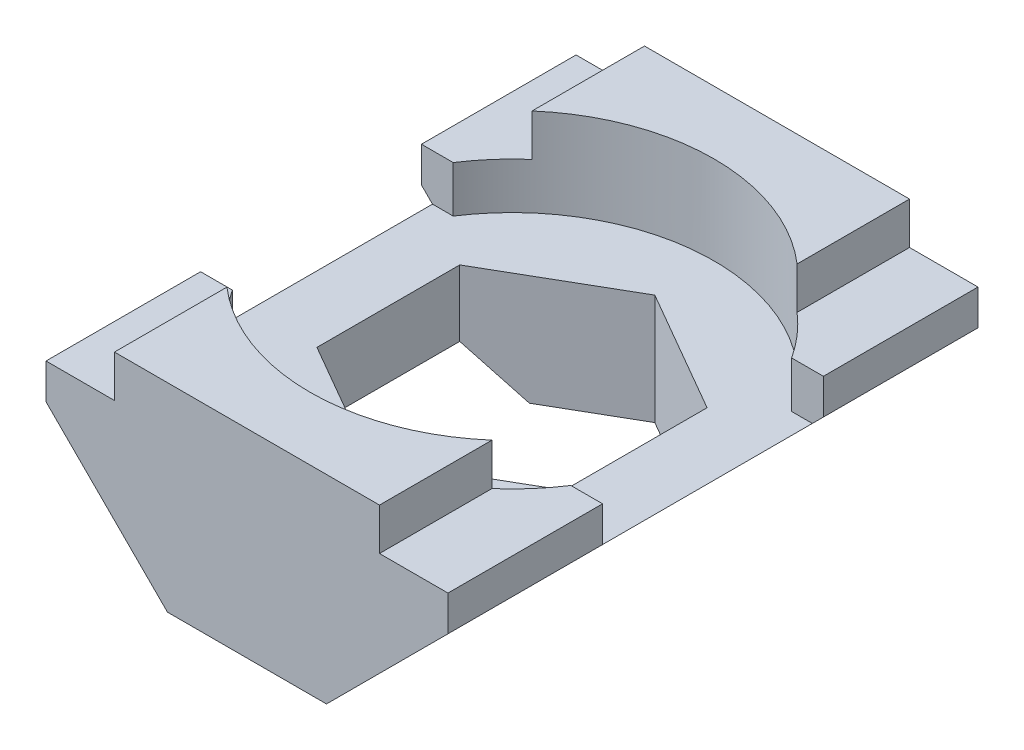
SolidWorks part; units mm, degrees
ref_plane "Front Plane" through (0, 0, 0) normal (0, 0, 1) x (1, 0, 0)
ref_plane "Top Plane" through (0, 0, 0) normal (0, 1, 0) x (1, 0, 0)
ref_plane "Right Plane" through (0, 0, 0) normal (1, 0, 0) x (0, 0, -1)
sketch "Sketch1" plane through (0, 0, 0) normal (0, 0, 1) x (1, 0, 0)
  line L0 (0, 0) -> (0, 5972.9771) construction
  line L1 (0, 0) -> (-5972.9771, 0) construction
  line L2 (0, 0) -> (0, 0.95)
  line L3 (0, 0.95) -> (6, 0.95)
  line L4 (6, 0.95) -> (6, 0)
  line L5 (6, 0) -> (7.55, 0)
  line L6 (7.55, 0) -> (7.55, -0.8)
  line L7 (7.55, -0.8) -> (4.8, -3.55)
  line L8 (4.8, -3.55) -> (1.2, -3.55)
  line L9 (1.2, -3.55) -> (-1.55, -0.8)
  line L10 (-1.55, -0.8) -> (-1.55, 0)
  line L11 (-1.55, 0) -> (0, 0)
  dimension "D1" = 0.95
  dimension "D2" = 1.55
  dimension "D3" = 1.55
  dimension "D4" = 6
  dimension "D5" = 0.8
  dimension "D6" = 0.8
  dimension "D7" = 135
  dimension "D8" = 135
  dimension "D9" = 4.5
extrude "Boss-Extrude1" add sketch "Sketch1" along normal blind 16
sketch "Sketch2" plane through (0, 0.95, 0) normal (0, 1, 0) x (1, 0, 0)
  line L0 (0, -8) -> (6, -8) construction
  line L1 (0, -16) -> (0, 0) construction
  line L2 (6, -16) -> (6, 0) construction
  circle A0 centre (3, -8) radius 4.575
  dimension "D1" = 9.15
extrude "Cut-Extrude1" cut sketch "Sketch2" against normal blind 2
sketch "Sketch3" plane through (0, -1.05, 0) normal (0, 1, 0) x (1, 0, 0)
  line L0 (3, -8) -> (3, -4.7668) construction
  line L1 (3, -4.7668) -> (0.2, -6.3834)
  line L2 (0.2, -6.3834) -> (0.2, -9.6166)
  line L3 (0.2, -9.6166) -> (3, -11.2332)
  line L4 (3, -11.2332) -> (5.8, -9.6166)
  line L5 (5.8, -9.6166) -> (5.8, -6.3834)
  line L6 (5.8, -6.3834) -> (3, -4.7668)
  circle A0 centre (3, -8) radius 2.8 construction
  dimension "D1" = 5.6
extrude "Cut-Extrude2" cut sketch "Sketch3" against normal through all
sketch "Sketch4" plane through (0, 0, 0) normal (0, 1, 0) x (1, 0, 0)
  line L0 (-1.55, -7.5224) -> (-1.55, 0) construction
  line L1 (-1.55, -5.5) -> (7.55, -5.5)
  line L2 (-1.55, -5.5) -> (-1.55, -10.5)
  line L3 (-1.55, -10.5) -> (7.55, -10.5)
  line L4 (7.55, -5.5) -> (7.55, -10.5)
  line L5 (7.55, -16) -> (7.55, -8.4776) construction
  line L6 (-1.55, -8) -> (3, -8) construction
  point P8 (-1.55, -8)
  dimension "D1" = 2.5
extrude "Cut-Extrude3" cut sketch "Sketch4" against normal up to surface (1.05 mm away)
sketch "Sketch5" plane through (0, 0.95, 0) normal (0, 1, 0) x (1, 0, 0)
  line L0 (7.55, -5.5) -> (7.55, 0) construction
  line L1 (-1.55, 0) -> (7.55, 0)
  line L2 (-1.55, 0) -> (-1.55, -2)
  line L3 (-1.55, -2) -> (7.55, -2)
  line L4 (7.55, 0) -> (7.55, -2)
  line L5 (7.55, -16) -> (7.55, -10.5) construction
  line L6 (-1.55, -16) -> (7.55, -16)
  line L7 (-1.55, -16) -> (-1.55, -14)
  line L8 (-1.55, -14) -> (7.55, -14)
  line L9 (7.55, -16) -> (7.55, -14)
  dimension "D1" = 2
  dimension "D2" = 2
extrude "Cut-Extrude4" cut sketch "Sketch5" against normal through all
